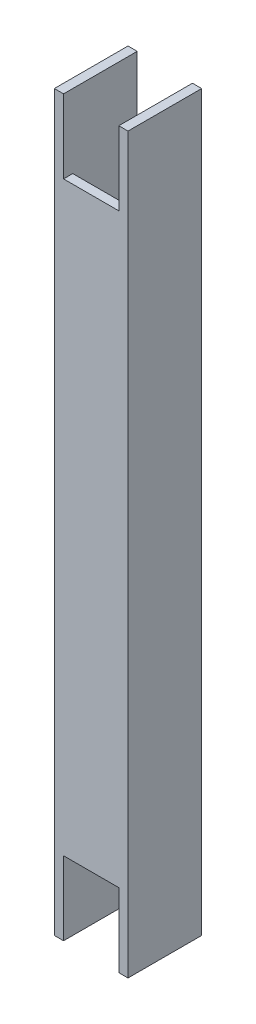
SolidWorks part; units mm, degrees
material "1060 Alloy"
ref_plane "Front Plane" through (0, 0, 0) normal (0, 0, 1) x (1, 0, 0)
ref_plane "Top Plane" through (0, 0, 0) normal (0, 1, 0) x (1, 0, 0)
ref_plane "Right Plane" through (0, 0, 0) normal (1, 0, 0) x (0, 0, -1)
sketch "Sketch1" plane through (0, 0, 0) normal (0, 1, 0) x (1, 0, 0)
  line L0 (0, 0) -> (25.4, 0)
  line L1 (25.4, 0) -> (25.4, 25.4)
  line L7 (0, 25.4) -> (0, 0)
  dimension "D1" = 25.4
  dimension "D2" = 25.4
  dimension "D3" = 25.4
extrude "Extrude-Thin1" add sketch "Sketch1" along normal blind 252.9 thin thin type one direction reverse wall 3.175
sketch "Sketch2" plane through (0, 0, -3.175) normal (0, 0, -1) x (-1, 0, 0)
  line L0 (-3.175, 126.45) -> (-22.225, 126.45) construction
  line L1 (-3.175, 252.9) -> (-3.175, 0) construction
  line L2 (-22.225, 252.9) -> (-22.225, 0) construction
  line L3 (-3.175, 25.4) -> (-22.225, 25.4)
  line L4 (-3.175, 252.9) -> (-22.225, 252.9)
  line L5 (-3.175, 252.9) -> (-3.175, 227.5)
  line L6 (-3.175, 227.5) -> (-22.225, 227.5)
  line L7 (-22.225, 252.9) -> (-22.225, 227.5)
  line L8 (-22.225, 0) -> (-22.225, 25.4)
  line L9 (-3.175, 0) -> (-22.225, 0)
  line L10 (-3.175, 0) -> (-3.175, 25.4)
extrude "Cut-Extrude1" cut sketch "Sketch2" against normal blind 3.175
